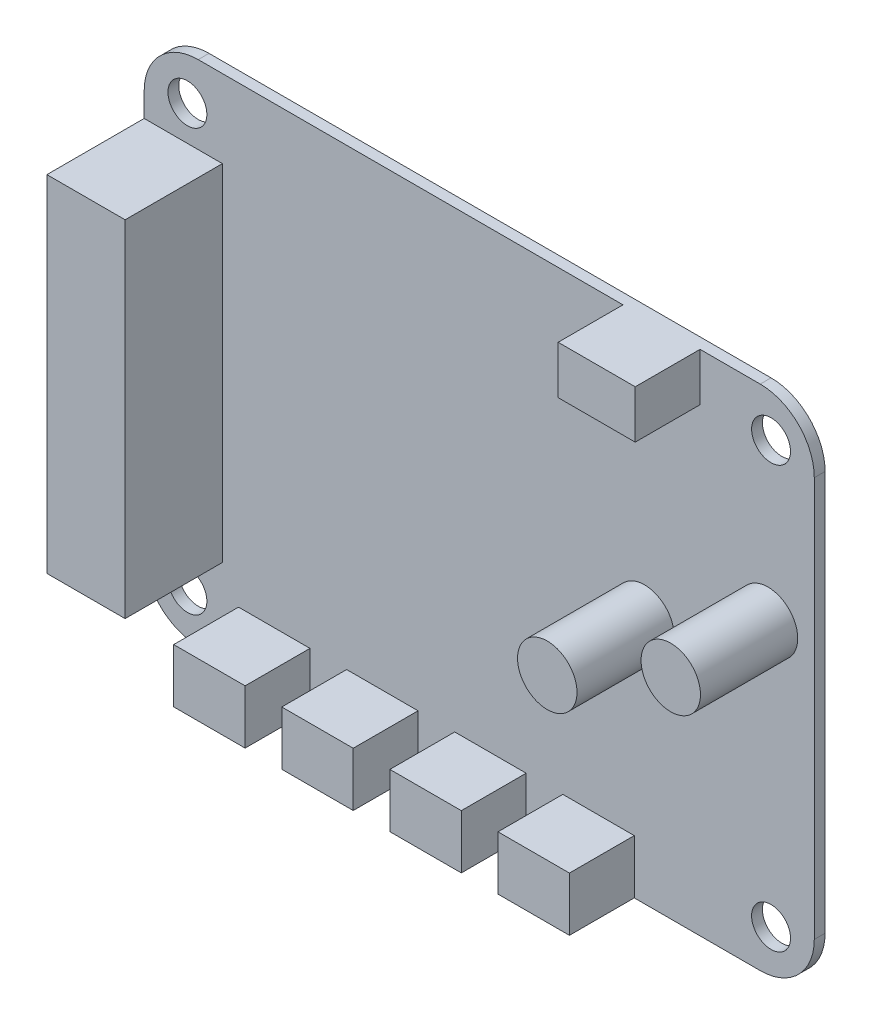
SolidWorks part; units mm, degrees
ref_plane "前视基准面" through (0, 0, 0) normal (0, 0, 1) x (1, 0, 0)
ref_plane "上视基准面" through (0, 0, 0) normal (0, 1, 0) x (1, 0, 0)
ref_plane "右视基准面" through (0, 0, 0) normal (1, 0, 0) x (0, 0, -1)
other "Configuration Table"
sketch "草图2" plane through (0, 0, 0) normal (0, 0, 1) x (1, 0, 0)
  line L0 (-54.9143, 0) -> (74.4329, 0) construction
  line L1 (0, 46.7572) -> (0, -45.7862) construction
  line L3 (-26, 23.5) -> (26, 23.5)
  line L4 (-31, 18.5) -> (-31, -18.5)
  line L5 (-26, -23.5) -> (26, -23.5)
  line L6 (31, 18.5) -> (31, -18.5)
  circle A0 centre (27, 19.5) radius 1.8
  circle A1 centre (-27, 19.5) radius 1.8
  circle A2 centre (27, -19.5) radius 1.8
  circle A3 centre (-27, -19.5) radius 1.8
  arc A4 (-26, 23.5) -> (-31, 18.5) centre (-26, 18.5) ccw
  arc A5 (-31, -18.5) -> (-26, -23.5) centre (-26, -18.5) ccw
  arc A6 (26, -23.5) -> (31, -18.5) centre (26, -18.5) ccw
  arc A7 (26, 23.5) -> (31, 18.5) centre (26, 18.5) cw
  point P22 (-31, 23.5)
  point P27 (31, -23.5)
  point P30 (31, 23.5)
  dimension "D3" = 3.6
  dimension "D6" = 5
  dimension "D1" = 47
  dimension "D2" = 62
  dimension "D4" = 39
  dimension "D5" = 54
extrude "凸台-拉伸1" add sketch "草图2" along normal blind 1
sketch "草图4" plane through (0, 0, 1) normal (0, 0, 1) x (1, 0, 0)
  line L0 (-31, 18.5) -> (-31, -18.5) construction
  line L1 (-31, 16.2839) -> (-23.7627, 16.2839)
  line L2 (-31, 16.2839) -> (-31, -15.6751)
  line L3 (-31, -15.6751) -> (-23.7627, -15.6751)
  line L4 (-23.7627, 16.2839) -> (-23.7627, -15.6751)
extrude "凸台-拉伸2" add sketch "草图4" along normal blind 9
sketch "草图5" plane through (0, 0, 1) normal (0, 0, 1) x (1, 0, 0)
  line L0 (-26, -23.5) -> (26, -23.5) construction
  line L1 (-22.2699, -23.5) -> (-15.6603, -23.5)
  line L2 (-22.2699, -23.5) -> (-22.2699, -18.5076)
  line L3 (-22.2699, -18.5076) -> (-15.6603, -18.5076)
  line L4 (-15.6603, -23.5) -> (-15.6603, -18.5076)
  line L5 (-12.2685, -23.5) -> (-12.2685, -18.5076)
  line L6 (-12.2685, -18.5076) -> (-5.6589, -18.5076)
  line L7 (-5.6589, -23.5) -> (-5.6589, -18.5076)
  line L8 (-12.2685, -23.5) -> (-5.6589, -23.5)
  line L9 (-2.2671, -23.5) -> (-2.2671, -18.5076)
  line L10 (-2.2671, -18.5076) -> (4.3426, -18.5076)
  line L11 (4.3426, -23.5) -> (4.3426, -18.5076)
  line L12 (-2.2671, -23.5) -> (4.3426, -23.5)
  line L13 (7.7344, -23.5) -> (7.7344, -18.5076)
  line L14 (7.7344, -18.5076) -> (14.344, -18.5076)
  line L15 (14.344, -23.5) -> (14.344, -18.5076)
  line L16 (7.7344, -23.5) -> (14.344, -23.5)
  line L17 (26, 23.5) -> (-26, 23.5) construction
  line L18 (20.4319, 23.5) -> (13.3004, 23.5)
  line L19 (20.4319, 23.5) -> (20.4319, 19.063)
  line L20 (20.4319, 19.063) -> (13.3004, 19.063)
  line L21 (13.3004, 23.5) -> (13.3004, 19.063)
  dimension "D1" = 4
extrude "凸台-拉伸3" add sketch "草图5" along normal blind 6
sketch "草图6" plane through (0, 0, 1) normal (0, 0, 1) x (1, 0, 0)
  circle A0 centre (26.7195, 4.8482) radius 2.75
  circle A1 centre (15.2934, -0.6872) radius 2.75
  dimension "D1" = 5.5
  dimension "D2" = 5.5
extrude "凸台-拉伸4" add sketch "草图6" along normal blind 9
sketch "草图7" plane through (0, 0, 0) normal (0, 0, -1) x (-1, 0, 0)
  line L5 (31, 18.5) -> (31, -18.5) construction
  line L10 (26, 14.0098) -> (31, 14.0098)
  line L11 (26, 14.0098) -> (26, -14.8446)
  line L12 (26, -14.8446) -> (31, -14.8446)
  line L13 (31, 14.0098) -> (31, -14.8446)
  dimension "D1" = 5
extrude "凸台-拉伸5" add sketch "草图7" along normal blind 0.4
